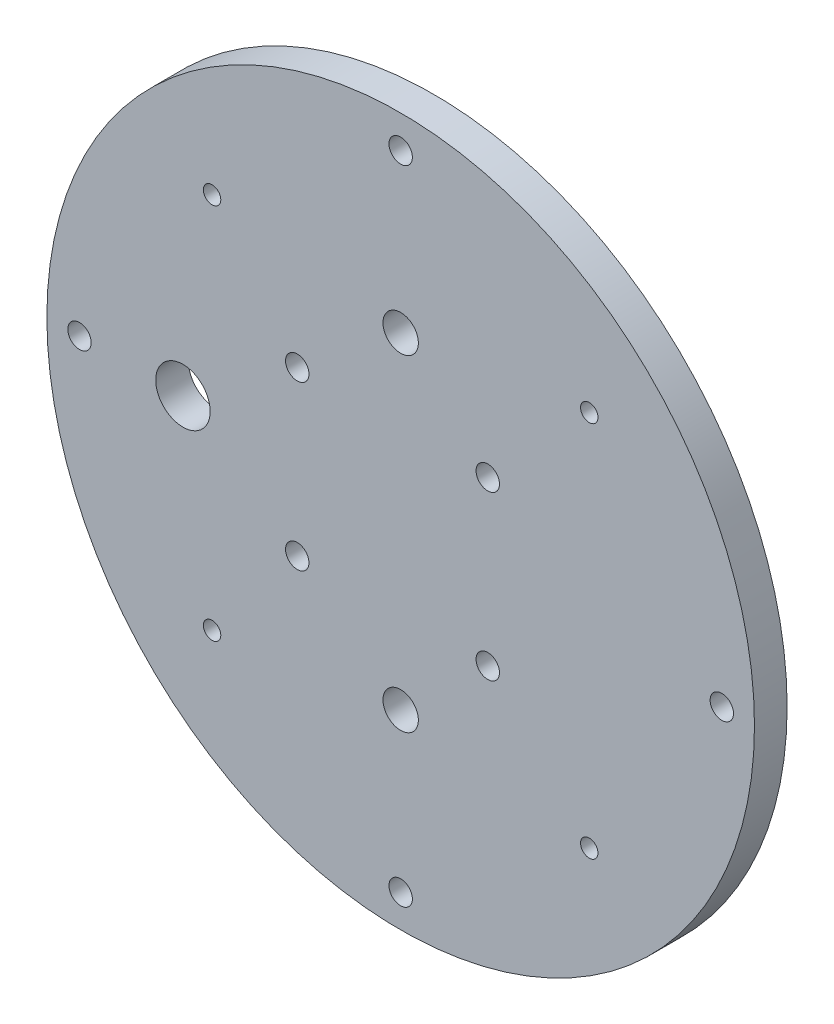
SolidWorks part; units mm, degrees
ref_plane "Front Plane" through (0, 0, 0) normal (0, 0, 1) x (1, 0, 0)
ref_plane "Top Plane" through (0, 0, 0) normal (0, 1, 0) x (1, 0, 0)
ref_plane "Right Plane" through (0, 0, 0) normal (1, 0, 0) x (0, 0, -1)
sketch "草圖1" plane through (0, 0, 0) normal (0, 0, 1) x (1, 0, 0)
  circle A0 centre (0, 0) radius 65
  circle A1 centre (34.6482, 34.6482) radius 1.6
  circle A2 centre (-34.6482, 34.6482) radius 1.6
  circle A3 centre (-34.6482, -34.6482) radius 1.6
  circle A4 centre (34.6482, -34.6482) radius 1.6
  circle A5 centre (59, 0) radius 2.15
  circle A6 centre (0, 59) radius 2.15
  circle A7 centre (-59, 0) radius 2.15
  circle A8 centre (0, -59) radius 2.15
  circle A9 centre (-19, 15) radius 2.15
  circle A10 centre (-19, -15) radius 2.15
  circle A11 centre (16, 15) radius 2.15
  circle A12 centre (16, -15) radius 2.15
  circle A13 centre (0, 30) radius 3.25
  circle A14 centre (0, -30) radius 3.25
  circle A15 centre (-40, 0) radius 5
extrude "填料-伸長1" add sketch "草圖1" along normal blind 6
